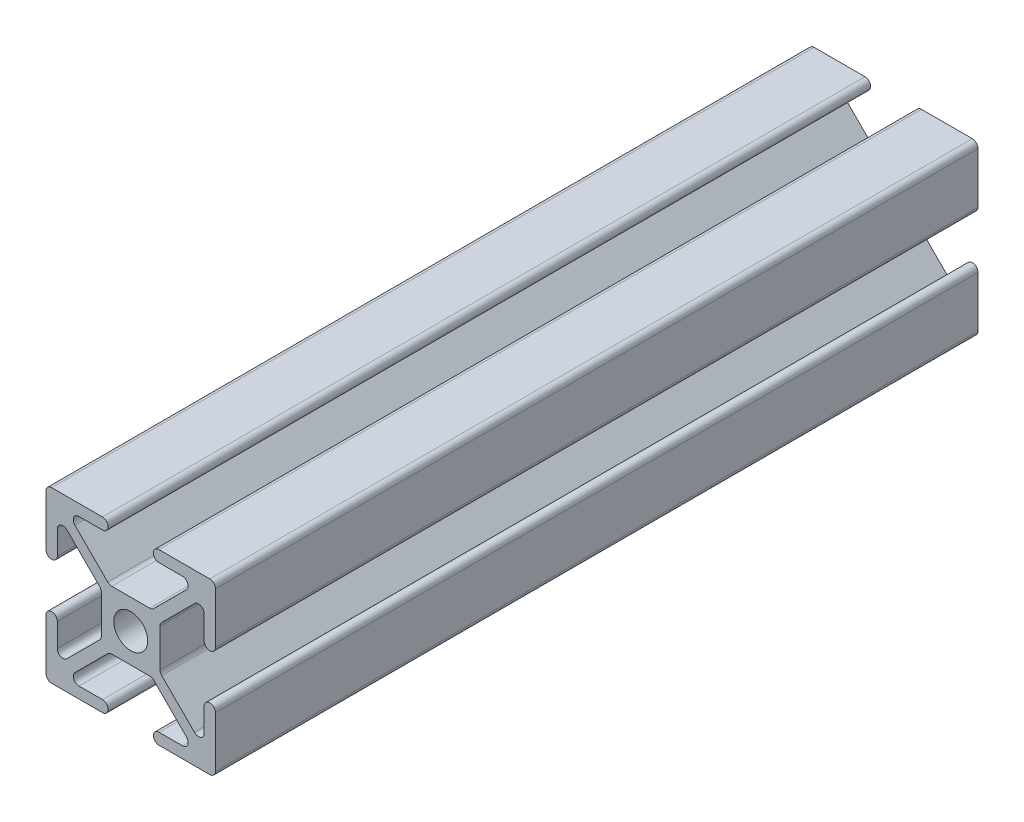
SolidWorks part; units mm, degrees
ref_plane "Alzado" through (0, 0, 0) normal (0, 0, 1) x (1, 0, 0)
ref_plane "Planta" through (0, 0, 0) normal (0, 1, 0) x (1, 0, 0)
ref_plane "Vista lateral" through (0, 0, 0) normal (1, 0, 0) x (0, 0, -1)
sketch "Croquis1" plane through (0, 0, 0) normal (0, 0, 1) x (1, 0, 0)
  line L1 (-14, 15) -> (14, 15)
  line L2 (-15, 14) -> (-15, -14)
  line L3 (-14, -15) -> (14, -15)
  line L4 (15, 14) -> (15, -14)
  line L5 (-15, 15) -> (15, -15) construction
  line L6 (-15, -15) -> (15, 15) construction
  arc A0 (-14, 15) -> (-15, 14) centre (-14, 14) ccw
  arc A1 (14, -15) -> (15, -14) centre (14, -14) ccw
  arc A2 (-14, -15) -> (-15, -14) centre (-14, -14) cw
  arc A3 (15, 14) -> (14, 15) centre (14, 14) ccw
  point P0 (0, 0)
  dimension "D3" = 1
  dimension "D4" = 1
  dimension "D1" = 30
  dimension "D2" = 30
extrude "Saliente-Extruir1" add sketch "Croquis1" against normal blind 190
sketch "Croquis2" plane through (0, 0, 0) normal (0, 0, 1) x (1, 0, 0)
  circle A0 centre (0, 0) radius 3
  dimension "D1" = 6
sketch "Croquis3" plane through (0, 0, 0) normal (0, 0, 1) x (1, 0, 0)
  line L0 (-15, 0) -> (15, 0) construction
  line L1 (4.0787, -5.4929) -> (9.8787, -11.2929)
  line L2 (-11.2929, 9.8787) -> (-5.4929, 4.0787)
  line L3 (-9.8787, 11.2929) -> (-4.0787, 5.4929)
  line L4 (-13, 9.1716) -> (-13, 5)
  line L5 (-15, 14) -> (-15, -14) construction
  line L6 (-5.2, 3.3716) -> (-5.2, -3.3716)
  line L7 (-9.1716, 13) -> (-5, 13)
  line L8 (9.8787, 11.2929) -> (4.0787, 5.4929)
  line L9 (11.2929, 9.8787) -> (5.4929, 4.0787)
  line L10 (-3.3716, 5.2) -> (3.3716, 5.2)
  line L11 (14, 15) -> (-14, 15) construction
  line L12 (13, 9.1716) -> (13, 5)
  line L13 (5.2, 3.3716) -> (5.2, -3.3716)
  line L14 (15, -14) -> (15, 14) construction
  line L15 (-9.1716, -13) -> (-5, -13)
  line L16 (-3.3716, -5.2) -> (3.3716, -5.2)
  line L17 (-14, -15) -> (14, -15) construction
  line L18 (-5.4929, -4.0787) -> (-11.2929, -9.8787)
  line L19 (5.4929, -4.0787) -> (11.2929, -9.8787)
  line L20 (-4.0787, -5.4929) -> (-9.8787, -11.2929)
  line L21 (5, -13) -> (9.1716, -13)
  line L22 (-13, -5) -> (-13, -9.1716)
  line L23 (13, -5) -> (13, -9.1716)
  line L24 (0, 15) -> (0, -5.2) construction
  line L34 (5, 13) -> (9.1716, 13)
  arc A0 (9.8787, 11.2929) -> (9.1716, 13) centre (9.1716, 12) ccw
  arc A1 (-9.8787, 11.2929) -> (-9.1716, 13) centre (-9.1716, 12) cw
  arc A2 (9.8787, 11.2929) -> (9.1716, 13) centre (9.1716, 12) ccw
  arc A3 (13, 9.1716) -> (11.2929, 9.8787) centre (12, 9.1716) ccw
  arc A4 (11.2929, -9.8787) -> (13, -9.1716) centre (12, -9.1716) ccw
  arc A5 (9.1716, -13) -> (9.8787, -11.2929) centre (9.1716, -12) ccw
  arc A6 (-9.1716, -13) -> (-9.8787, -11.2929) centre (-9.1716, -12) cw
  arc A7 (-11.2929, -9.8787) -> (-13, -9.1716) centre (-12, -9.1716) cw
  arc A8 (-13, 9.1716) -> (-11.2929, 9.8787) centre (-12, 9.1716) cw
  arc A9 (-4.0787, -5.4929) -> (-3.3716, -5.2) centre (-3.3716, -6.2) cw
  arc A10 (3.3716, -5.2) -> (4.0787, -5.4929) centre (3.3716, -6.2) cw
  arc A11 (5.4929, -4.0787) -> (5.2, -3.3716) centre (6.2, -3.3716) cw
  arc A12 (5.2, 3.3716) -> (5.4929, 4.0787) centre (6.2, 3.3716) cw
  arc A13 (3.3716, 5.2) -> (4.0787, 5.4929) centre (3.3716, 6.2) ccw
  arc A14 (-3.3716, 5.2) -> (-4.0787, 5.4929) centre (-3.3716, 6.2) cw
  arc A15 (-5.4929, -4.0787) -> (-5.2, -3.3716) centre (-6.2, -3.3716) ccw
  arc A16 (-5.2, 3.3716) -> (-5.4929, 4.0787) centre (-6.2, 3.3716) ccw
  circle A17 centre (-14, -5) radius 1
  circle A18 centre (-14, 5) radius 1
  circle A19 centre (-5, -14) radius 1
  circle A20 centre (5, -14) radius 1
  circle A21 centre (14, 5) radius 1
  circle A22 centre (14, -5) radius 1
  circle A23 centre (-5, 14) radius 1
  circle A24 centre (5, 14) radius 1
  point P20 (-11.5858, -13)
  point P30 (-13, -11.5858)
  point P43 (-3.7858, -5.2)
  point P50 (3.7858, -5.2)
  point P53 (5.2, -3.7858)
  point P62 (-5.2, -3.7858)
  line M2 (-15, 14) -> (-15, -14)
  line M4 (-14, -15) -> (14, -15)
  line M6 (15, -14) -> (15, 14)
  line M8 (14, 15) -> (-14, 15)
  dimension "D6" = 9.8
  dimension "D7" = 2
  dimension "D12" = 2
  dimension "D19" = 1
  dimension "D2" = 1
  dimension "D3" = 1
  dimension "D4" = 1
  dimension "D16" = 1
  dimension "D5" = 2
  dimension "D8" = 9.8
  dimension "D9" = 2
  dimension "D10" = 9.8
  dimension "D11" = 9.8
  dimension "D15" = 1
  dimension "D20" = 1
  dimension "D23" = 1
  dimension "D24" = 1
  dimension "D27" = 1
  dimension "D28" = 1
extrude "Cortar-Extruir1" cut sketch "Croquis2" against normal through all
extrude "Cortar-Extruir3" cut sketch "Croquis3" against normal through all contours A18 A17 L22 A7 L18 A15 L6 A16 L2 A8 L4 M2 | A24 A23 L7 A1 L3 A14 L10 A13 L8 A0 L34 M8 | A20 L21 A5 L1 A10 L16 A9 L20 A6 L15 A19 M4 | A22 A21 L12 A3 L9 A12 L13 A11 L19 A4 L23 M6
sketch "Croquis4" plane through (0, 15, 0) normal (0, 1, 0) x (1, 0, 0)
  line L1 (15, 0) -> (-18.1276, 0)
  line L2 (15, 0) -> (15, 30)
  line L3 (15, 30) -> (-18.1276, 30)
  line L4 (-18.1276, 0) -> (-18.1276, 30)
extrude "Cortar-Extruir4" cut sketch "Croquis4" against normal blind 38
sketch "Croquis5" plane through (15, 0, 0) normal (1, 0, 0) x (0, 0, -1)
  line L0 (190, -15) -> (30, -15) construction
  line L1 (30, 15) -> (55, 15)
  line L2 (30, 15) -> (30, -15)
  line L3 (30, -15) -> (55, -15)
  line L4 (55, 15) -> (55, -15)
  line L5 (190, 5) -> (190, 14) construction
  dimension "D1" = 135
extrude "Cortar-Extruir5" cut sketch "Croquis5" against normal blind 30
